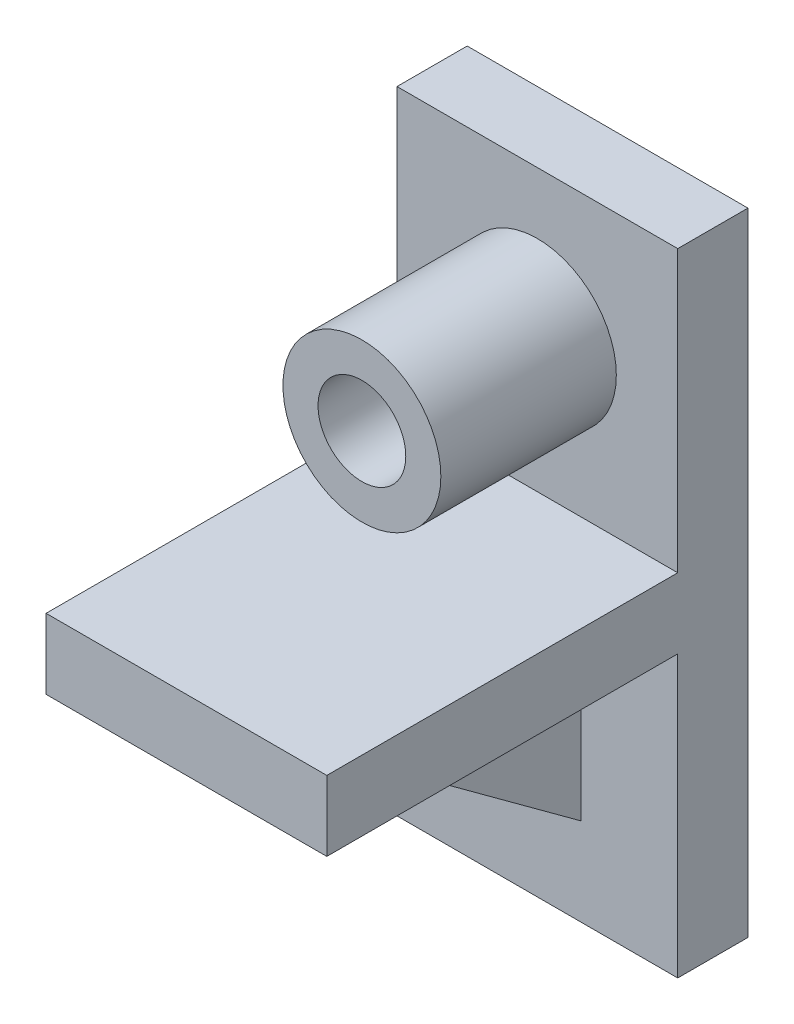
SolidWorks part; units mm, degrees
ref_plane "Front Plane" through (0, 0, 0) normal (0, 0, 1) x (1, 0, 0)
ref_plane "Top Plane" through (0, 0, 0) normal (0, 1, 0) x (1, 0, 0)
ref_plane "Right Plane" through (0, 0, 0) normal (1, 0, 0) x (0, 0, -1)
sketch "Sketch2" plane through (0, 0, 0) normal (0, 0, 1) x (1, 0, 0)
  line L1 (-20.7531, 12.5188) -> (11.2469, 12.5188)
  line L2 (-20.7531, 12.5188) -> (-20.7531, -59.4812)
  line L3 (-20.7531, -59.4812) -> (11.2469, -59.4812)
  line L4 (11.2469, 12.5188) -> (11.2469, -59.4812)
  dimension "D1" = 32
  dimension "D2" = 72
extrude "Boss-Extrude1" add sketch "Sketch2" along normal blind 8
sketch "Sketch3" plane through (0, 0, 8) normal (0, 0, 1) x (1, 0, 0)
  line L0 (-4.7531, -59.4812) -> (-4.7531, -27.4812) construction
  line L1 (-20.7531, -59.4812) -> (11.2469, -59.4812) construction
  line L2 (-20.7531, -27.4812) -> (11.2469, -27.4812)
  line L3 (-20.7531, 12.5188) -> (-20.7531, -59.4812) construction
  line L4 (11.2469, -59.4812) -> (11.2469, 12.5188) construction
  line L5 (11.2469, -27.4812) -> (11.2469, -19.4812)
  line L6 (11.2469, -19.4812) -> (-20.7531, -19.4812)
  line L7 (-20.7531, -19.4812) -> (-20.7531, -27.4812)
  line L8 (-4.7531, 12.5188) -> (-4.7531, -3.4812) construction
  line L9 (11.2469, 12.5188) -> (-20.7531, 12.5188) construction
  circle A0 centre (-4.7531, -3.4812) radius 5
  circle A1 centre (-4.7531, -3.4812) radius 9
  dimension "D1" = 10
  dimension "D2" = 18
extrude "Boss-Extrude2" add sketch "Sketch3" along normal blind 20
sketch "Sketch4" plane through (0, 0, 28) normal (0, 0, 1) x (1, 0, 0)
  line L1 (-20.7531, -19.4812) -> (11.2469, -19.4812)
  line L2 (-20.7531, -19.4812) -> (-20.7531, -27.4812)
  line L3 (-20.7531, -27.4812) -> (11.2469, -27.4812)
  line L4 (11.2469, -19.4812) -> (11.2469, -27.4812)
extrude "Boss-Extrude3" add sketch "Sketch4" along normal blind 20
ref_plane "Plane1" through (-4.7531, 0, 0) normal (-1, 0, 0) x (0, 0, 1)
sketch "Sketch5" plane through (-4.7531, 0, 0) normal (-1, 0, 0) x (0, 0, 1)
  line L0 (38, -27.4812) -> (8, -49.4812)
  line L1 (48, -27.4812) -> (8, -27.4812) construction
  line L2 (8, -27.4812) -> (8, -59.4812) construction
  line L3 (48, -19.4812) -> (48, -27.4812) construction
  line L4 (8, -59.4812) -> (0, -59.4812) construction
  dimension "D1" = 10
  dimension "D2" = 10
rib "Rib1" sketch "Sketch5" sketch "Sketch5" thickness 10 extrusion direction parallel to sketch draft on no parameters "D1"=10
